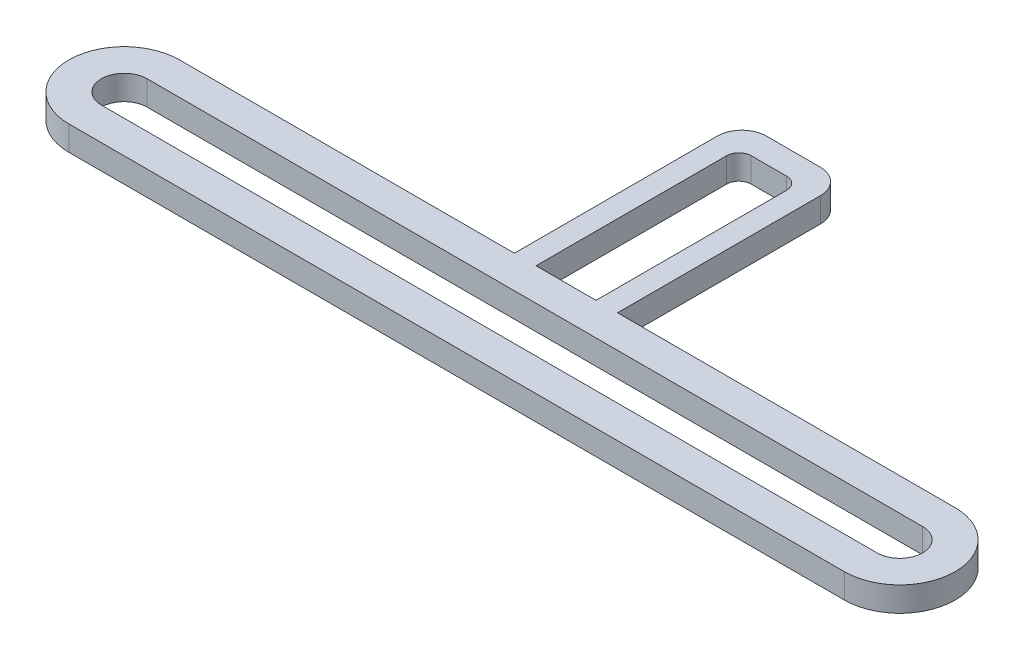
SolidWorks part; units mm, degrees
material "1060 Alloy"
ref_plane "Front Plane" through (0, 0, 0) normal (0, 0, 1) x (1, 0, 0)
ref_plane "Top Plane" through (0, 0, 0) normal (0, 1, 0) x (1, 0, 0)
ref_plane "Right Plane" through (0, 0, 0) normal (1, 0, 0) x (0, 0, -1)
sketch "Sketch1" plane through (0, 0, 0) normal (0, 1, 0) x (1, 0, 0)
  line L0 (-40.0346, 0.005) -> (40.0232, 0.005) construction
  line L5 (-40.0346, 5.7236) -> (-5.4769, 5.7236)
  line L6 (-40.0346, -5.7135) -> (40.0232, -5.7135)
  line L7 (-40.0346, 0.005) -> (40.0232, 0.005) construction
  line L8 (-40.0346, 2.3627) -> (40.0232, 2.3627)
  line L9 (-40.0346, -2.3526) -> (40.0232, -2.3526)
  line L10 (2.3675, 5.7236) -> (2.9464, 5.7236)
  line L20 (5.1716, 5.7236) -> (40.0232, 5.7236)
  line L21 (-3.2387, 5.7236) -> (2.9464, 5.7236)
  line L22 (-5.4769, 5.7236) -> (-5.4769, 26.6619)
  line L23 (-2.9369, 29.2019) -> (2.6316, 29.2019)
  line L25 (5.1716, 5.7236) -> (5.1716, 26.6619)
  line L26 (-3.2387, 5.7236) -> (2.9464, 5.7236)
  line L27 (-3.2387, 5.7236) -> (-3.2387, 25.3919)
  line L28 (-1.9687, 26.6619) -> (1.6764, 26.6619)
  line L29 (2.9464, 5.7236) -> (2.9464, 25.3919)
  line L30 (-3.2387, 5.7236) -> (-2.6824, 5.7236)
  arc A0 (-40.0346, 5.7236) -> (-40.0346, -5.7135) centre (-40.0346, 0.005) ccw
  arc A1 (40.0232, -5.7135) -> (40.0232, 5.7236) centre (40.0232, 0.005) ccw
  arc A2 (-40.0346, 2.3627) -> (-40.0346, -2.3526) centre (-40.0346, 0.005) ccw
  arc A3 (40.0232, -2.3526) -> (40.0232, 2.3627) centre (40.0232, 0.005) ccw
  arc A6 (2.6316, 29.2019) -> (5.1716, 26.6619) centre (2.6316, 26.6619) cw
  arc A7 (-2.9369, 29.2019) -> (-5.4769, 26.6619) centre (-2.9369, 26.6619) ccw
  arc A8 (1.6764, 26.6619) -> (2.9464, 25.3919) centre (1.6764, 25.3919) cw
  arc A9 (-1.9687, 26.6619) -> (-3.2387, 25.3919) centre (-1.9687, 25.3919) ccw
  point P2 (-0.0057, 0.005)
  point P4 (-0.0057, 0.005)
extrude "Boss-Extrude10" add sketch "Sketch1" along normal mid plane 2.54 contours L5 L22 A7 L23 A6 L25 L20 A1 L6 A0 | L27 A9 L28 A8 L29 L26 | L9 A3 L8 A2
